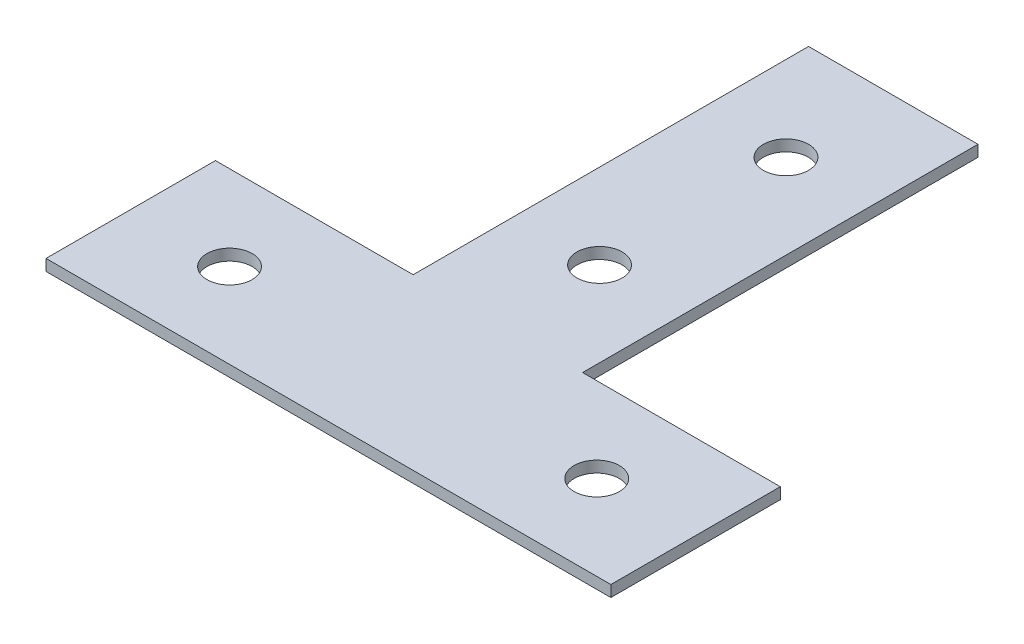
SolidWorks part; units mm, degrees
ref_plane "Front Plane" through (0, 0, 0) normal (0, 0, 1) x (1, 0, 0)
ref_plane "Top Plane" through (0, 0, 0) normal (0, 1, 0) x (1, 0, 0)
ref_plane "Right Plane" through (0, 0, 0) normal (1, 0, 0) x (0, 0, -1)
sketch "Sketch1" plane through (0, 0, 0) normal (0, 1, 0) x (1, 0, 0)
  line L1 (17.5, 50) -> (32.5, 50)
  line L2 (32.5, 50) -> (32.5, 15)
  line L3 (32.5, 15) -> (50, 15)
  line L4 (50, 15) -> (50, 0)
  line L5 (50, 0) -> (0, 0)
  line L6 (0, 15) -> (0, 0)
  line L7 (17.5, 15) -> (0, 15)
  line L8 (17.5, 50) -> (17.5, 15)
  dimension "D1" = 50
  dimension "D2" = 15
  dimension "D3" = 17.5
  dimension "D4" = 35
extrude "Boss-Extrude1" add sketch "Sketch1" along normal blind 1
sketch "Sketch2" plane through (0, 1, 0) normal (0, 1, 0) x (1, 0, 0)
  line L0 (0, 15) -> (0, 0) construction
  line L1 (0, 0) -> (50, 0) construction
  circle A0 centre (41.25, 7.5) radius 2
  circle A1 centre (25, 40.5) radius 2
  circle A2 centre (25, 24) radius 2
  circle A3 centre (8.75, 7.5) radius 2
  dimension "D2" = 4
  dimension "D5" = 8.75
  dimension "D6" = 41.25
  dimension "D7" = 7.5
  dimension "D8" = 7.5
  dimension "D9" = 25
  dimension "D10" = 24
  dimension "D11" = 40.5
  dimension "D12" = 16.5
extrude "Cut-Extrude1" cut sketch "Sketch2" against normal through all both and the other way through all
